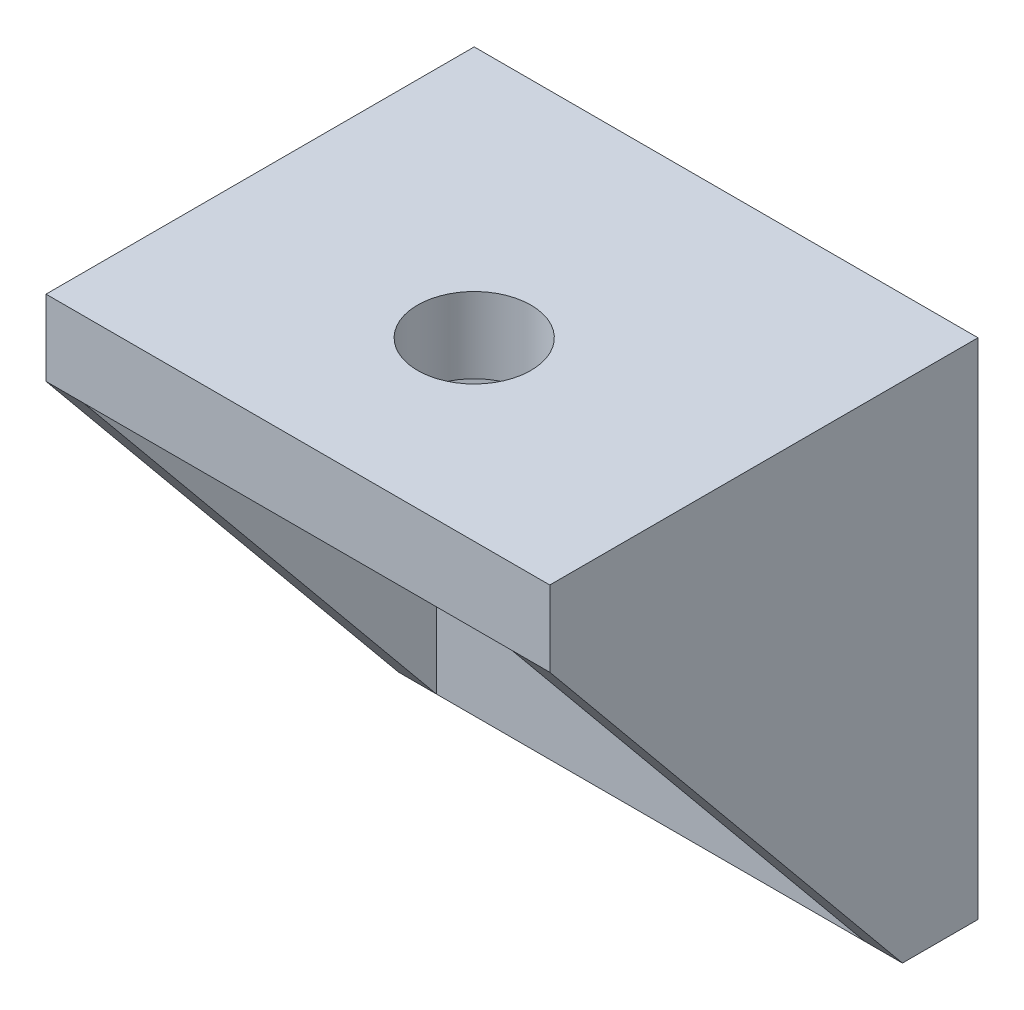
SolidWorks part; units mm, degrees
ref_plane "정면" through (0, 0, 0) normal (0, 0, 1) x (1, 0, 0)
ref_plane "윗면" through (0, 0, 0) normal (0, 1, 0) x (1, 0, 0)
ref_plane "우측면" through (0, 0, 0) normal (1, 0, 0) x (0, 0, -1)
sketch "스케치1" plane through (0, 0, 0) normal (0, 0, 1) x (1, 0, 0)
  line L7 (-10, 10) -> (10, 10)
  line L8 (-10, 10) -> (-10, -10)
  line L9 (-10, -10) -> (10, -10)
  line L10 (10, 10) -> (10, -10)
  line L11 (-10, 10) -> (10, -10) construction
  line L12 (-10, -10) -> (10, 10) construction
  point P1 (0, 0)
  dimension "D1" = 20
  dimension "D2" = 20
extrude "보스-돌출1" add sketch "스케치1" along normal blind 17
sketch "스케치2" plane through (10, 0, 0) normal (1, 0, 0) x (0, 0, -1)
  line L0 (-17, 7) -> (-3, -10)
  line L1 (-17, -10) -> (-17, 10) construction
  line L2 (-17, -10) -> (0, -10) construction
  line L3 (-3, -10) -> (-17, -10)
  line L4 (-17, -10) -> (-17, 7)
  line L5 (-17, 10) -> (0, 10) construction
  line L6 (0, -10) -> (0, 10) construction
  dimension "D1" = 3
  dimension "D2" = 3
extrude "컷-돌출1" cut sketch "스케치2" against normal blind 20
sketch "스케치3" plane through (0, 0, 17) normal (0, 0, 1) x (1, 0, 0)
  line L0 (-10, 7) -> (10, 7) construction
  line L1 (-8.5, 7) -> (8.5, 7)
  line L2 (-8.5, 7) -> (-8.5, -10)
  line L3 (-8.5, -10) -> (8.5, -10)
  line L4 (8.5, 7) -> (8.5, -10)
  line L5 (-10, -10) -> (10, -10) construction
  line L6 (-10, -10) -> (-10, 7) construction
  line L7 (10, -10) -> (10, 7) construction
  dimension "D1" = 1.5
  dimension "D2" = 1.5
extrude "컷-돌출2" cut sketch "스케치3" against normal up to vertex (14 mm away)
hole_wizard "M4 여유 구멍1" positions "스케치4" profile "스케치5" hole size "M4" standard "KS" end condition through all
sketch "스케치4" plane through (0, 7, 0) normal (0, -1, 0) x (-1, 0, 0)
  line L1 (-8.5, -3) -> (-8.5, -17) construction
  line L2 (-8.5, -17) -> (8.5, -17) construction
  point P0 (0, -10)
  dimension "D1" = 7
  dimension "D2" = 8.5
sketch "스케치5" plane through (0, 7, 10) normal (1, 0, 0) x (0, 0, -1)
  line L0 (0, 0) -> (0, 3)
  line L1 (0, 3) -> (2.25, 3)
  line L2 (2.25, 3) -> (2.25, 0)
  line L5 (2.25, 0) -> (0, 0)
  line L11 (0, -6.35) -> (0, 107.95) construction
  dimension "관통 구멍 지름" = 4.5
  dimension "관통 구멍 깊이" = 3
sketch "스케치9" plane through (0, 0, 0) normal (0, 0, -1) x (-1, 0, 0)
  line L0 (-10, 10) -> (10, 10) construction
  line L1 (10, 10) -> (10, -10) construction
  circle A0 centre (0, 1.5) radius 2.05
  dimension "D1" = 4.1
  dimension "D2" = 8.5
  dimension "D3" = 10
extrude "보스-돌출3" add sketch "스케치9" along normal blind 5
